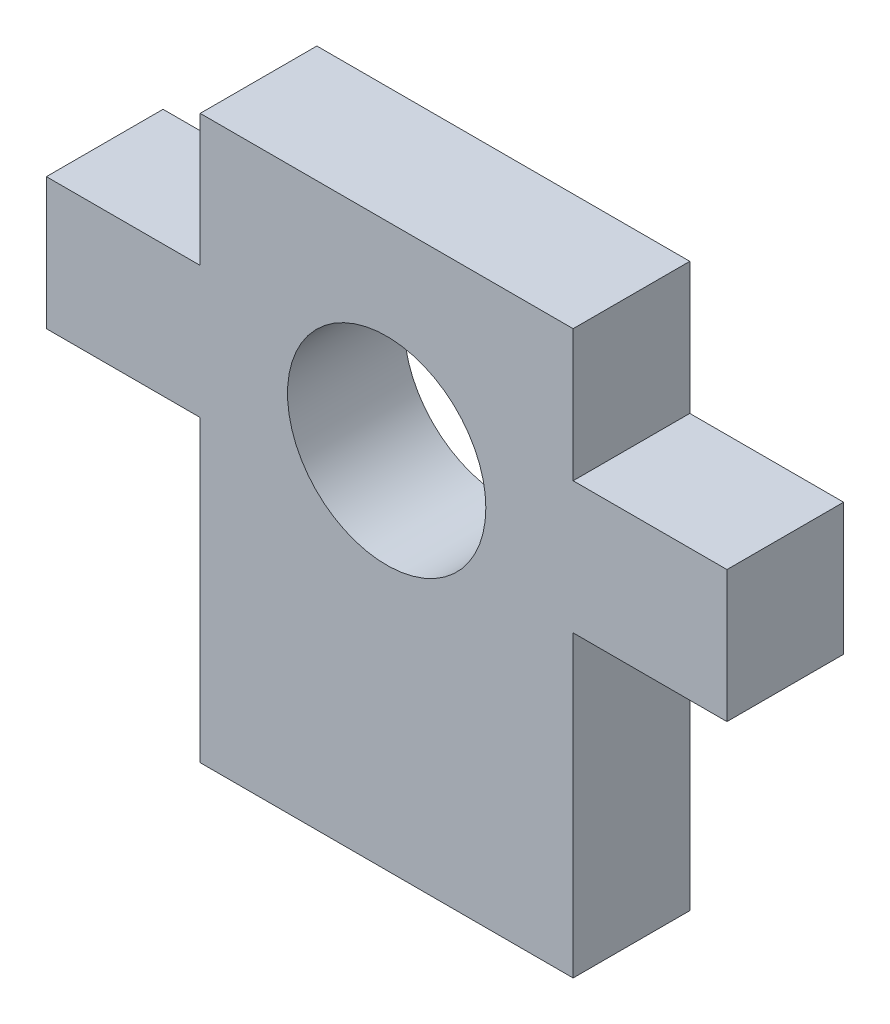
SolidWorks part; units mm, degrees
ref_plane "Front Plane" through (0, 0, 0) normal (0, 0, 1) x (1, 0, 0)
ref_plane "Top Plane" through (0, 0, 0) normal (0, 1, 0) x (1, 0, 0)
ref_plane "Right Plane" through (0, 0, 0) normal (1, 0, 0) x (0, 0, -1)
sketch "Sketch1" plane through (0, 0, 0) normal (0, 0, 1) x (1, 0, 0)
  line L1 (-14.385, -21.69) -> (14.385, -21.69)
  line L2 (-14.385, -21.69) -> (-14.385, 21.69)
  line L3 (-14.385, 21.69) -> (14.385, 21.69)
  line L4 (14.385, -21.69) -> (14.385, 21.69)
  line L5 (-14.385, -21.69) -> (14.385, 21.69) construction
  line L6 (-14.385, 21.69) -> (14.385, -21.69) construction
  line L7 (-26.25, 11.53) -> (26.25, 11.53)
  line L8 (-26.25, 11.53) -> (-26.25, 1.37)
  line L9 (-26.25, 1.37) -> (26.25, 1.37)
  line L10 (26.25, 11.53) -> (26.25, 1.37)
  line L11 (-26.25, 11.53) -> (26.25, 1.37) construction
  line L12 (-26.25, 1.37) -> (26.25, 11.53) construction
  point P0 (0, 0)
  point P6 (0, 6.45)
  dimension "D1" = 28.77
  dimension "D2" = 43.38
  dimension "D3" = 52.5
  dimension "D4" = 10.16
  dimension "D5" = 10.16
extrude "Boss-Extrude1" add sketch "Sketch1" along normal blind 9 contours L8 L9 L2 L7 | L9 L2 L1 L4 | L2 L9 L4 L7 | L2 L7 L4 L3 | L10 L7 L4 L9
sketch "Sketch3" plane through (0, 0, 9) normal (0, 0, 1) x (1, 0, 0)
  line L0 (-14.385, 21.69) -> (14.385, 21.69) construction
  circle A0 centre (0, 6.35) radius 7.65
  dimension "D1" = 15.3
  dimension "D2" = 15.34
extrude "Cut-Extrude1" cut sketch "Sketch3" against normal through all
